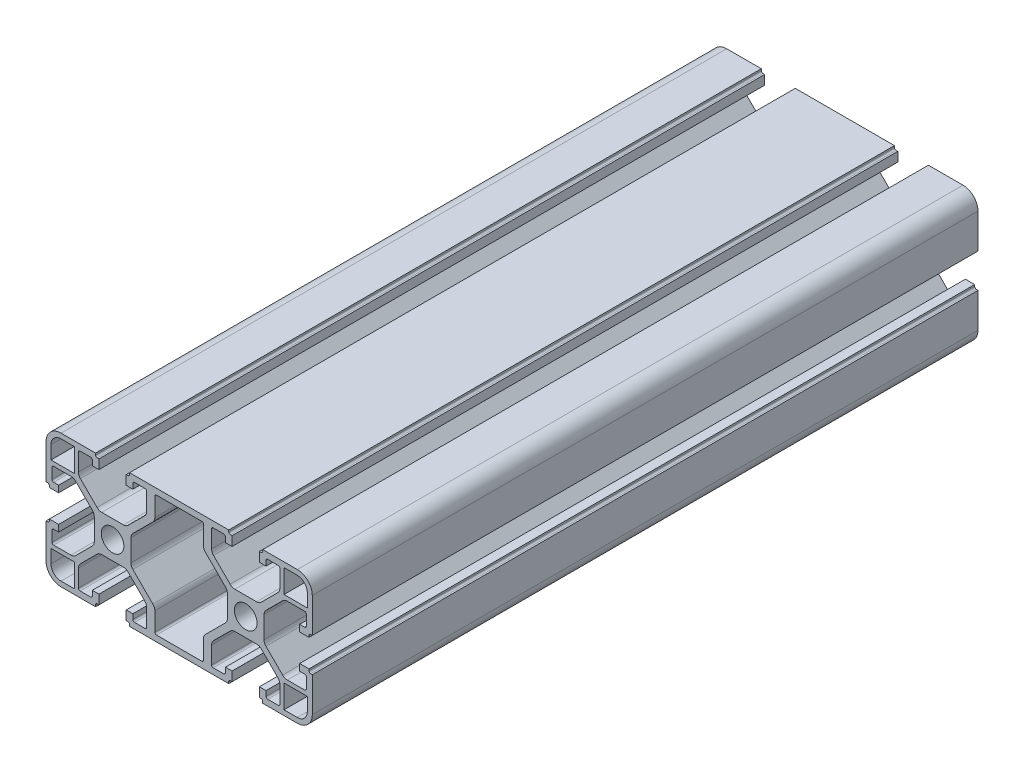
SolidWorks part; units mm, degrees
material "1060 合金"
ref_plane "前视基准面" through (0, 0, 0) normal (0, 0, 1) x (1, 0, 0)
ref_plane "上视基准面" through (0, 0, 0) normal (0, 1, 0) x (1, 0, 0)
ref_plane "右视基准面" through (0, 0, 0) normal (1, 0, 0) x (0, 0, -1)
sketch "草图1" plane through (0, 0, 0) normal (0, 0, 1) x (1, 0, 0)
  line L0 (-18.5, 15.5) -> (-18.5, 11.5)
  line L1 (-3.2574, 5.5) -> (3.2574, 5.5)
  line L2 (-5.5, 3.2574) -> (-5.5, -3.2574)
  line L3 (-3.2574, -5.5) -> (3.2574, -5.5)
  line L4 (5.5, 3.2574) -> (5.5, -3.2574)
  line L5 (-5.5, 5.5) -> (5.5, -5.5) construction
  line L6 (-5.5, -5.5) -> (5.5, 5.5) construction
  line L7 (-15.5, 20) -> (-5.1, 20)
  line L8 (-20, 15.5) -> (-20, 5.1)
  line L9 (-15.5, -20) -> (-5.1, -20)
  line L10 (60, 15.5) -> (60, 5.1)
  line L11 (36.7426, 5.5) -> (43.2574, 5.5)
  line L12 (34.5, 3.2574) -> (34.5, -3.2574)
  line L13 (36.7426, -5.5) -> (43.2574, -5.5)
  line L14 (45.5, 3.2574) -> (45.5, -3.2574)
  line L15 (34.5, 5.5) -> (45.5, -5.5) construction
  line L16 (34.5, -5.5) -> (45.5, 5.5) construction
  line L21 (-11.5, 18.5) -> (-15.5, 18.5)
  line L22 (-18.5, 11.5) -> (-11.5, 11.5)
  line L27 (6.0858, 4.6716) -> (12.1142, 10.7)
  line L28 (4.6716, 6.0858) -> (9.6642, 11.0784)
  line L33 (20, 42.3045) -> (20, -35.7395) construction
  line L34 (58.5, 15.5) -> (58.5, 11.5)
  line L39 (51.5, 18.5) -> (55.5, 18.5)
  line L40 (51.5, 18.5) -> (51.5, 11.5)
  line L41 (-9.6642, 11.0784) -> (-4.6716, 6.0858)
  line L47 (58.5, 11.5) -> (51.5, 11.5)
  line L48 (27.3, 17.7) -> (27.3, 12.1142)
  line L53 (33.9142, 4.6716) -> (27.8858, 10.7)
  line L54 (35.3284, 6.0858) -> (30.3358, 11.0784)
  line L58 (-10.25, 20.75) -> (-10.25, 20) construction
  line L59 (-20.25, 20.25) -> (-10.75, 10.75) construction
  line L60 (-20.25, 10.75) -> (-10.25, 20.75) construction
  line L65 (29.75, 17.7) -> (29.75, 12.4926)
  line L66 (30.25, 18.2) -> (33.4, 18.2)
  line L67 (-11.0784, 9.6642) -> (-6.0858, 4.6716)
  line L68 (33.9, 17.7) -> (33.9, 16.2)
  line L69 (33.9, 16.2) -> (35.9, 16.2)
  line L70 (34.9, 19.5) -> (34.9, 20)
  line L71 (35.9, 19) -> (35.4, 19)
  line L72 (35.9, 16.2) -> (35.9, 19)
  line L73 (51.0784, 9.6642) -> (46.0858, 4.6716)
  line L74 (52.4926, 10.25) -> (57.7, 10.25)
  line L76 (10.25, 17.7) -> (10.25, 12.4926)
  line L79 (12.7, 17.7) -> (12.7, 12.1142)
  line L81 (13.2, 18.2) -> (26.8, 18.2)
  line L83 (45.1, 19.5) -> (45.1, 20)
  line L84 (9.75, 18.2) -> (6.6, 18.2)
  line L85 (6.1, 17.7) -> (6.1, 16.2)
  line L86 (6.1, 16.2) -> (4.1, 16.2)
  line L87 (4.1, 16.2) -> (4.1, 19)
  line L88 (4.1, 19) -> (4.6, 19)
  line L89 (5.1, 19.5) -> (5.1, 20)
  line L90 (0, 23.211) -> (0, -33.1546) construction
  line L91 (-4.1, 16.2) -> (-6.1, 16.2)
  line L92 (-6.1, 16.2) -> (-6.1, 17.7)
  line L93 (-6.6, 18.2) -> (-9.75, 18.2)
  line L94 (-4.1, 16.2) -> (-4.1, 19)
  line L95 (-4.1, 19) -> (-4.656, 19)
  line L96 (-4.656, 19) -> (-4.6, 19)
  line L97 (-5.1, 19.5) -> (-5.1, 20)
  line L98 (-10.25, 17.7) -> (-10.25, 12.4926)
  line L99 (44.1, 19) -> (44.656, 19)
  line L100 (44.1, 16.2) -> (44.1, 19)
  line L101 (-11.5, 18.5) -> (-11.5, 11.5)
  line L102 (-12.4926, 10.25) -> (-17.7, 10.25)
  line L103 (44.1, 16.2) -> (46.1, 16.2)
  line L104 (46.1, 16.2) -> (46.1, 17.7)
  line L105 (46.6, 18.2) -> (49.75, 18.2)
  line L106 (50.25, 17.7) -> (50.25, 12.4926)
  line L107 (49.6642, 11.0784) -> (44.6716, 6.0858)
  line L108 (-37.1629, 0) -> (-20, 0) construction
  line L109 (-11.5, -18.5) -> (-15.5, -18.5)
  line L110 (-11.5, -18.5) -> (-11.5, -11.5)
  line L111 (-18.5, -11.5) -> (-11.5, -11.5)
  line L112 (-18.5, -15.5) -> (-18.5, -11.5)
  line L113 (-10.25, -17.7) -> (-10.25, -12.4926)
  line L114 (-12.4926, -10.25) -> (-17.7, -10.25)
  line L115 (-9.6642, -11.0784) -> (-4.6716, -6.0858)
  line L116 (-11.0784, -9.6642) -> (-6.0858, -4.6716)
  line L117 (-4.1, -16.2) -> (-4.1, -19)
  line L118 (-4.1, -16.2) -> (-6.1, -16.2)
  line L119 (-6.1, -16.2) -> (-6.1, -17.7)
  line L120 (-6.6, -18.2) -> (-9.75, -18.2)
  line L121 (-4.1, -19) -> (-4.656, -19)
  line L122 (-5.1, -19.5) -> (-5.1, -20)
  line L123 (10.25, -17.7) -> (10.25, -12.4926)
  line L124 (12.7, -17.7) -> (12.7, -12.1142)
  line L125 (4.6716, -6.0858) -> (9.6642, -11.0784)
  line L126 (6.0858, -4.6716) -> (12.1142, -10.7)
  line L127 (13.2, -18.2) -> (26.8, -18.2)
  line L128 (5.1, -19.5) -> (5.1, -20)
  line L129 (4.1, -19) -> (4.6, -19)
  line L130 (4.1, -16.2) -> (4.1, -19)
  line L131 (6.1, -16.2) -> (4.1, -16.2)
  line L132 (6.1, -17.7) -> (6.1, -16.2)
  line L133 (9.75, -18.2) -> (6.6, -18.2)
  line L134 (35.3284, -6.0858) -> (30.3358, -11.0784)
  line L135 (34.9, -19.5) -> (34.9, -20)
  line L136 (35.9, -19) -> (35.4, -19)
  line L137 (35.9, -16.2) -> (35.9, -19)
  line L138 (33.9, -16.2) -> (35.9, -16.2)
  line L139 (33.9, -17.7) -> (33.9, -16.2)
  line L140 (30.25, -18.2) -> (33.4, -18.2)
  line L141 (29.75, -17.7) -> (29.75, -12.4926)
  line L142 (33.9142, -4.6716) -> (27.8858, -10.7)
  line L143 (27.3, -17.7) -> (27.3, -12.1142)
  line L144 (52.4926, -10.25) -> (57.7, -10.25)
  line L145 (44.1, -19) -> (44.656, -19)
  line L146 (45.1, -19.5) -> (45.1, -20)
  line L147 (44.1, -16.2) -> (44.1, -19)
  line L148 (44.1, -16.2) -> (46.1, -16.2)
  line L149 (46.1, -16.2) -> (46.1, -17.7)
  line L150 (46.6, -18.2) -> (49.75, -18.2)
  line L151 (50.25, -17.7) -> (50.25, -12.4926)
  line L152 (49.6642, -11.0784) -> (44.6716, -6.0858)
  line L153 (51.0784, -9.6642) -> (46.0858, -4.6716)
  line L154 (58.5, -15.5) -> (58.5, -11.5)
  line L155 (58.5, -11.5) -> (51.5, -11.5)
  line L156 (51.5, -18.5) -> (51.5, -11.5)
  line L157 (51.5, -18.5) -> (55.5, -18.5)
  line L158 (45.1, 20) -> (55.5, 20)
  line L159 (5.1, 20) -> (34.9, 20)
  line L160 (5.1, -20) -> (34.9, -20)
  line L161 (45.1, -20) -> (55.5, -20)
  line L162 (-16.2, 4.1) -> (-16.2, 6.1)
  line L163 (-16.2, 6.1) -> (-17.7, 6.1)
  line L164 (-18.2, 6.6) -> (-18.2, 9.75)
  line L165 (-19.5, 5.1) -> (-20, 5.1)
  line L166 (-19, 4.1) -> (-19, 4.656)
  line L167 (-16.2, 4.1) -> (-19, 4.1)
  line L168 (-18.2, -6.6) -> (-18.2, -9.75)
  line L169 (-16.2, -6.1) -> (-17.7, -6.1)
  line L170 (-16.2, -4.1) -> (-16.2, -6.1)
  line L171 (-16.2, -4.1) -> (-19, -4.1)
  line L172 (-19.5, -5.1) -> (-20, -5.1)
  line L173 (-19, -4.1) -> (-19, -4.656)
  line L174 (59.5, -5.1) -> (60, -5.1)
  line L175 (59, -4.1) -> (59, -4.656)
  line L176 (56.2, -4.1) -> (59, -4.1)
  line L177 (56.2, -4.1) -> (56.2, -6.1)
  line L178 (56.2, -6.1) -> (57.7, -6.1)
  line L179 (58.2, -6.6) -> (58.2, -9.75)
  line L180 (59.5, 5.1) -> (60, 5.1)
  line L181 (59, 4.1) -> (59, 4.656)
  line L182 (56.2, 4.1) -> (59, 4.1)
  line L183 (56.2, 4.1) -> (56.2, 6.1)
  line L184 (56.2, 6.1) -> (57.7, 6.1)
  line L185 (58.2, 6.6) -> (58.2, 9.75)
  line L186 (60, -5.1) -> (60, -15.5)
  line L187 (-20, -5.1) -> (-20, -15.5)
  line L188 (-5.5, 0) -> (60, 0) construction
  circle A0 centre (0, 0) radius 3.4
  circle A1 centre (40, 0) radius 3.4
  arc A2 (-15.5, 20) -> (-20, 15.5) centre (-15.5, 15.5) ccw
  arc A3 (60, 15.5) -> (55.5, 20) centre (55.5, 15.5) ccw
  arc A4 (55.5, -20) -> (60, -15.5) centre (55.5, -15.5) ccw
  arc A5 (-20, -15.5) -> (-15.5, -20) centre (-15.5, -15.5) ccw
  arc A10 (-15.5, 18.5) -> (-18.5, 15.5) centre (-15.5, 15.5) ccw
  arc A11 (-9.75, 18.2) -> (-10.25, 17.7) centre (-9.75, 17.7) ccw
  arc A12 (-6.1, 17.7) -> (-6.6, 18.2) centre (-6.6, 17.7) ccw
  arc A13 (-5.1, 19.5) -> (-4.6, 19) centre (-4.6, 19.5) ccw
  arc A14 (4.6, 19) -> (5.1, 19.5) centre (4.6, 19.5) ccw
  arc A15 (6.6, 18.2) -> (6.1, 17.7) centre (6.6, 17.7) ccw
  arc A16 (10.25, 17.7) -> (9.75, 18.2) centre (9.75, 17.7) ccw
  arc A17 (9.6642, 11.0784) -> (10.25, 12.4926) centre (8.25, 12.4926) ccw
  arc A18 (-10.25, 12.4926) -> (-9.6642, 11.0784) centre (-8.25, 12.4926) ccw
  arc A20 (-11.0784, 9.6642) -> (-12.4926, 10.25) centre (-12.4926, 8.25) ccw
  arc A21 (12.1142, 10.7) -> (12.7, 12.1142) centre (10.7, 12.1142) ccw
  arc A22 (-4.6716, 6.0858) -> (-3.2574, 5.5) centre (-3.2574, 7.5) ccw
  arc A23 (3.2574, 5.5) -> (4.6716, 6.0858) centre (3.2574, 7.5) ccw
  arc A24 (13.2, 18.2) -> (12.7, 17.7) centre (13.2, 17.7) ccw
  arc A25 (6.0858, 4.6716) -> (5.5, 3.2574) centre (7.5, 3.2574) ccw
  arc A26 (-5.5, 3.2574) -> (-6.0858, 4.6716) centre (-7.5, 3.2574) ccw
  arc A27 (58.5, 15.5) -> (55.5, 18.5) centre (55.5, 15.5) ccw
  arc A28 (26.8, 18.2) -> (27.3, 17.7) centre (26.8, 17.7) cw
  arc A29 (27.8858, 10.7) -> (27.3, 12.1142) centre (29.3, 12.1142) cw
  arc A30 (33.9142, 4.6716) -> (34.5, 3.2574) centre (32.5, 3.2574) cw
  arc A31 (36.7426, 5.5) -> (35.3284, 6.0858) centre (36.7426, 7.5) cw
  arc A32 (30.3358, 11.0784) -> (29.75, 12.4926) centre (31.75, 12.4926) cw
  arc A33 (29.75, 17.7) -> (30.25, 18.2) centre (30.25, 17.7) cw
  arc A34 (33.4, 18.2) -> (33.9, 17.7) centre (33.4, 17.7) cw
  arc A35 (35.4, 19) -> (34.9, 19.5) centre (35.4, 19.5) cw
  arc A36 (45.5, 3.2574) -> (46.0858, 4.6716) centre (47.5, 3.2574) cw
  arc A37 (44.6716, 6.0858) -> (43.2574, 5.5) centre (43.2574, 7.5) cw
  arc A38 (51.0784, 9.6642) -> (52.4926, 10.25) centre (52.4926, 8.25) cw
  arc A39 (45.1, 19.5) -> (44.6, 19) centre (44.6, 19.5) cw
  arc A40 (46.1, 17.7) -> (46.6, 18.2) centre (46.6, 17.7) cw
  arc A41 (49.75, 18.2) -> (50.25, 17.7) centre (49.75, 17.7) cw
  arc A42 (50.25, 12.4926) -> (49.6642, 11.0784) centre (48.25, 12.4926) cw
  arc A43 (-18.5, -15.5) -> (-15.5, -18.5) centre (-15.5, -15.5) ccw
  arc A44 (-11.0784, -9.6642) -> (-12.4926, -10.25) centre (-12.4926, -8.25) cw
  arc A45 (-10.25, -12.4926) -> (-9.6642, -11.0784) centre (-8.25, -12.4926) cw
  arc A46 (-4.6716, -6.0858) -> (-3.2574, -5.5) centre (-3.2574, -7.5) cw
  arc A47 (-5.5, -3.2574) -> (-6.0858, -4.6716) centre (-7.5, -3.2574) cw
  arc A48 (-6.1, -17.7) -> (-6.6, -18.2) centre (-6.6, -17.7) cw
  arc A49 (-9.75, -18.2) -> (-10.25, -17.7) centre (-9.75, -17.7) cw
  arc A50 (-5.1, -19.5) -> (-4.6, -19) centre (-4.6, -19.5) cw
  arc A51 (12.1142, -10.7) -> (12.7, -12.1142) centre (10.7, -12.1142) cw
  arc A52 (9.6642, -11.0784) -> (10.25, -12.4926) centre (8.25, -12.4926) cw
  arc A53 (6.0858, -4.6716) -> (5.5, -3.2574) centre (7.5, -3.2574) cw
  arc A54 (3.2574, -5.5) -> (4.6716, -6.0858) centre (3.2574, -7.5) cw
  arc A55 (4.6, -19) -> (5.1, -19.5) centre (4.6, -19.5) cw
  arc A56 (6.6, -18.2) -> (6.1, -17.7) centre (6.6, -17.7) cw
  arc A57 (13.2, -18.2) -> (12.7, -17.7) centre (13.2, -17.7) cw
  arc A58 (10.25, -17.7) -> (9.75, -18.2) centre (9.75, -17.7) cw
  arc A59 (33.9142, -4.6716) -> (34.5, -3.2574) centre (32.5, -3.2574) ccw
  arc A60 (36.7426, -5.5) -> (35.3284, -6.0858) centre (36.7426, -7.5) ccw
  arc A61 (35.4, -19) -> (34.9, -19.5) centre (35.4, -19.5) ccw
  arc A62 (33.4, -18.2) -> (33.9, -17.7) centre (33.4, -17.7) ccw
  arc A63 (29.75, -17.7) -> (30.25, -18.2) centre (30.25, -17.7) ccw
  arc A64 (30.3358, -11.0784) -> (29.75, -12.4926) centre (31.75, -12.4926) ccw
  arc A65 (27.8858, -10.7) -> (27.3, -12.1142) centre (29.3, -12.1142) ccw
  arc A66 (26.8, -18.2) -> (27.3, -17.7) centre (26.8, -17.7) ccw
  arc A67 (51.0784, -9.6642) -> (52.4926, -10.25) centre (52.4926, -8.25) ccw
  arc A68 (45.1, -19.5) -> (44.6, -19) centre (44.6, -19.5) ccw
  arc A69 (46.1, -17.7) -> (46.6, -18.2) centre (46.6, -17.7) ccw
  arc A70 (49.75, -18.2) -> (50.25, -17.7) centre (49.75, -17.7) ccw
  arc A71 (50.25, -12.4926) -> (49.6642, -11.0784) centre (48.25, -12.4926) ccw
  arc A72 (45.5, -3.2574) -> (46.0858, -4.6716) centre (47.5, -3.2574) ccw
  arc A73 (44.6716, -6.0858) -> (43.2574, -5.5) centre (43.2574, -7.5) ccw
  arc A74 (55.5, -18.5) -> (58.5, -15.5) centre (55.5, -15.5) ccw
  arc A75 (-17.7, 6.1) -> (-18.2, 6.6) centre (-17.7, 6.6) cw
  arc A76 (-18.2, 9.75) -> (-17.7, 10.25) centre (-17.7, 9.75) cw
  arc A77 (-19.5, 5.1) -> (-19, 4.6) centre (-19.5, 4.6) cw
  arc A78 (-18.2, -9.75) -> (-17.7, -10.25) centre (-17.7, -9.75) ccw
  arc A79 (-17.7, -6.1) -> (-18.2, -6.6) centre (-17.7, -6.6) ccw
  arc A80 (-19.5, -5.1) -> (-19, -4.6) centre (-19.5, -4.6) ccw
  arc A81 (59.5, -5.1) -> (59, -4.6) centre (59.5, -4.6) cw
  arc A82 (57.7, -6.1) -> (58.2, -6.6) centre (57.7, -6.6) cw
  arc A83 (58.2, -9.75) -> (57.7, -10.25) centre (57.7, -9.75) cw
  arc A84 (59.5, 5.1) -> (59, 4.6) centre (59.5, 4.6) ccw
  arc A85 (57.7, 6.1) -> (58.2, 6.6) centre (57.7, 6.6) ccw
  arc A86 (58.2, 9.75) -> (57.7, 10.25) centre (57.7, 9.75) ccw
  point P104 (-4.628, 19)
  point P306 (-20, -5.1)
  dimension "D1" = 6.8
  dimension "D8" = 6.8
  dimension "D13" = 9
  dimension "D14" = 9
  dimension "D15" = 9
  dimension "D16" = 9
  dimension "D17" = 7
  dimension "D18" = 23.2574
  dimension "D19" = 40
  dimension "D20" = 1
  dimension "D65" = 1.5
  dimension "D66" = 6
  dimension "D23" = 1
  dimension "D24" = 1
  dimension "D25" = 1
  dimension "D27" = 1
  dimension "D30" = 1
  dimension "D31" = 4
  dimension "D32" = 4
  dimension "D33" = 2
  dimension "D34" = 4
  dimension "D41" = 4
  dimension "D42" = 4
  dimension "D43" = 1
  dimension "D38" = 4
  dimension "D39" = 4
  dimension "D47" = 15.3284
  dimension "D2" = 5.5
  dimension "D3" = 5.5
  dimension "D4" = 20
  dimension "D5" = 20
  dimension "D7" = 5.5
  dimension "D9" = 10.3358
  dimension "D12" = 20
  dimension "D21" = 7
  dimension "D22" = 7
  dimension "D26" = 1
  dimension "D28" = 1.5
  dimension "D29" = 10.25
  dimension "D35" = 7.5074
  dimension "D36" = 1
  dimension "D37" = 1
  dimension "D40" = 7.5074
  dimension "D44" = 20.5
  dimension "D45" = 15.3284
  dimension "D46" = 2.45
  dimension "D48" = 1.8
  dimension "D51" = 1.8
  dimension "D52" = 4.1
  dimension "D53" = 5.1
  dimension "D56" = 4.1
  dimension "D57" = 1.8
  dimension "D58" = 5.1
  dimension "D59" = 1
  dimension "D60" = 2
  dimension "D61" = 2
  dimension "D62" = 2
extrude "凸台-拉伸1" add sketch "草图1" along normal blind 200
